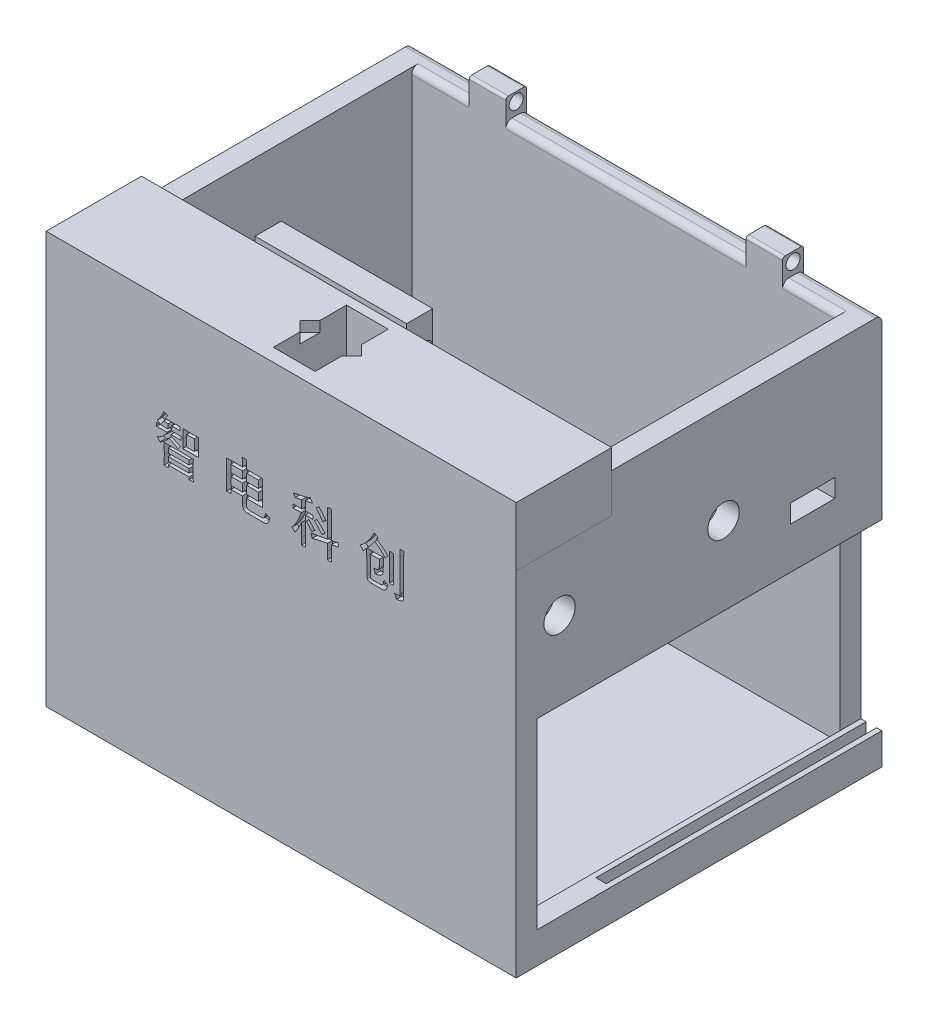
SolidWorks part; units mm, degrees
ref_plane "前视基准面" through (0, 0, 0) normal (0, 0, 1) x (1, 0, 0)
ref_plane "上视基准面" through (0, 0, 0) normal (0, 1, 0) x (1, 0, 0)
ref_plane "右视基准面" through (0, 0, 0) normal (1, 0, 0) x (0, 0, -1)
other "Configuration Table"
sketch "草图1" plane through (0, 0, 0) normal (0, 1, 0) x (1, 0, 0)
  line L1 (0, 0) -> (90, 0)
  line L2 (0, 0) -> (0, 70)
  line L3 (0, 70) -> (90, 70)
  line L4 (90, 0) -> (90, 70)
  dimension "D1" = 90
  dimension "D2" = 70
extrude "凸台-拉伸1" add sketch "草图1" along normal blind 75 contours L2 L1 L4 L3
shell "抽壳1" thickness 4
ref_plane "基准面2" through (0, 75, 0) normal (0, 1, 0) x (1, 0, 0)
sketch "草图2" plane through (0, 75, 0) normal (0, 1, 0) x (1, 0, 0)
  line L0 (0, 70) -> (90, 70) construction
  line L1 (0, 0) -> (0, 70) construction
  line L4 (4, 66) -> (86, 66) construction
  line L8 (15, 70) -> (22, 70)
  line L9 (15, 70) -> (15, 66)
  line L10 (15, 66) -> (22, 66)
  line L11 (22, 70) -> (22, 66)
  dimension "D1" = 15
  dimension "D2" = 7
extrude "凸台-拉伸2" add sketch "草图2" along normal blind 4
fillet "圆角3" radius 0.5 2 edges at (18.5, 79, -70) (18.5, 79, -66)
sketch "草图4" plane through (22, 0, 0) normal (1, 0, 0) x (0, 0, -1)
  line L0 (66, 78.5) -> (70, 78.5) construction
  line L1 (70, 78.5) -> (70, 75) construction
  line L2 (38.5, 75) -> (-38.5, 75) construction
  arc A0 (70, 78.5) -> (69.5, 79) centre (69.5, 78.5) ccw construction
  circle A1 centre (68, 77.3) radius 1.35
  dimension "D1" = 2.7
  dimension "D2" = 2.3
extrude "切除-拉伸1" cut sketch "草图4" against normal through all contours A1
ref_plane "基准面3" through (45, 0, 0) normal (-1, 0, 0) x (0, 0, 1)
mirror "镜向2" about plane through (45, 0, 0) normal (-1, 0, 0) of "切除-拉伸1", "凸台-拉伸2", "圆角3"
sketch "草图6" plane through (90, 0, 0) normal (1, 0, 0) x (0, 0, -1)
  line L1 (0, 75) -> (18.2564, 75)
  line L2 (0, 75) -> (0, 78.8304)
  line L3 (0, 78.8304) -> (18.2564, 78.8304)
  line L4 (18.2564, 75) -> (18.2564, 78.8304)
  line L5 (0, 75) -> (18.2564, 75)
  line L6 (0, 75) -> (0, 67.5141)
  line L7 (0, 67.5141) -> (18.2564, 67.5141)
  line L8 (18.2564, 75) -> (18.2564, 67.5141)
  line M3 (70, 75) -> (0, 75)
  line M4 (0, 75) -> (0, 0)
extrude "凸台-拉伸3" add sketch "草图6" along normal through all and the other way through all contours L4 L3 L2 M3 | L8 L7 M3 M4
sketch "草图7" plane through (90, 0, 0) normal (1, 0, 0) x (0, 0, -1)
  line L0 (0, 67.5141) -> (0, 0) construction
  line L5 (4, 6) -> (70, 6)
  line L6 (4, 6) -> (4, 41)
  line L7 (4, 41) -> (70, 41)
  line L8 (70, 6) -> (70, 41)
  line L9 (0, 0) -> (70, 0) construction
  dimension "D1" = 66
  dimension "D2" = 4
  dimension "D3" = 6
  dimension "D4" = 35
extrude "切除-拉伸2" cut sketch "草图7" against normal blind 4
sketch "草图8" plane through (0, 78.8304, 0) normal (0, 1, 0) x (1, 0, 0)
  line L0 (45, 38.5) -> (45, -38.5) construction
  line L1 (41, 16.5) -> (49, 16.5)
  line L2 (45, 16.5) -> (45, 2.5)
  line L3 (41, 2.5) -> (49, 2.5)
  line L4 (49, 16.5) -> (49, 2.5)
  line L5 (90, 0) -> (0, 0) construction
  line L6 (41, 16.5) -> (41, 2.5)
  dimension "D1" = 14
  dimension "D2" = 4
  dimension "D3" = 2.5
extrude "切除-拉伸3" cut sketch "草图8" against normal blind 17 contours L4 L3 L6 L1
ref_plane "基准面4" through (4, 75, -66) normal (0, 0, -1) x (-1, 0, 0)
sketch "草图10" plane through (4, 0, 0) normal (1, 0, 0) x (0, 0, -1)
  line L0 (0, 67.5141) -> (0, 0) construction
  line L1 (12, 62) -> (36, 62) construction
  line L2 (12, 62) -> (12, 50) construction
  line L3 (12, 50) -> (36, 50) construction
  line L4 (36, 62) -> (36, 50) construction
  line L5 (0, 0) -> (70, 0) construction
  line L7 (36, 62) -> (41, 62)
  line L8 (36, 62) -> (36, 50)
  line L9 (36, 50) -> (41, 50)
  line L10 (41, 62) -> (41, 50)
  line L11 (12, 62) -> (7, 62)
  line L12 (12, 62) -> (12, 50)
  line L13 (12, 50) -> (7, 50)
  line L14 (7, 62) -> (7, 50)
  dimension "D1" = 24
  dimension "D2" = 12
  dimension "D3" = 12
  dimension "D4" = 50
  dimension "D5" = 5
  dimension "D6" = 5
extrude "凸台-拉伸4" add sketch "草图10" along normal blind 29 contours L12 L11 L14 L13 | L8 L7 L10 L9
sketch "草图13" plane through (33, 0, 0) normal (1, 0, 0) x (0, 0, -1)
  line L0 (12, 56) -> (36, 56) construction
  line L1 (24, 56) -> (24, 61.1681) construction
  line L2 (39.7, 56) -> (41, 56) construction
  line L4 (36, 50) -> (41, 50)
  line L5 (41, 50) -> (41, 62)
  line L6 (41, 62) -> (36, 62)
  line L7 (36, 62) -> (36, 50)
  line L8 (36, 50) -> (41, 50)
  line L9 (41, 50) -> (41, 62)
  line L10 (41, 62) -> (36, 62)
  line L11 (36, 62) -> (36, 50)
  line L12 (7, 50) -> (12, 50)
  line L13 (12, 50) -> (12, 62)
  line L14 (12, 62) -> (7, 62)
  line L15 (7, 62) -> (7, 50)
  line L16 (7, 50) -> (12, 50)
  line L17 (12, 50) -> (12, 62)
  line L18 (12, 62) -> (7, 62)
  line L19 (7, 62) -> (7, 50)
  circle A0 centre (39.7, 56) radius 1.25
  circle A1 centre (8.3, 56) radius 1.25
  point P14 (41, 56)
  dimension "D3" = 2.5
  dimension "D4" = 1.3
  dimension "D1" = 0
  dimension "D2" = 0
extrude "切除-拉伸5" cut sketch "草图13" against normal blind 10 contours L9 A0 | A1
sketch "草图14" plane through (0, 0, -4) normal (0, 0, -1) x (-1, 0, 0)
  line L0 (-45, -38.5) -> (-45, 38.5) construction
  line L1 (-87, 46) -> (-57, 46)
  line L2 (-87, 46) -> (-87, 42)
  line L3 (-87, 42) -> (-57, 42)
  line L4 (-57, 46) -> (-57, 42)
  line L5 (0, 0) -> (-90, 0) construction
  dimension "D1" = 4
  dimension "D2" = 30
  dimension "D3" = 42
  dimension "D4" = 42
extrude "凸台-拉伸5" add sketch "草图14" along normal blind 25
sketch "草图15" plane through (0, 78.8304, 0) normal (0, 1, 0) x (1, 0, 0)
  line L0 (41, 9.5) -> (49, 9.5) construction
  line L1 (41, 16.5) -> (41, 2.5) construction
  line L2 (49, 16.5) -> (49, 2.5) construction
  line L3 (41, 2.5) -> (49, 2.5) construction
  line L4 (45, 2.5) -> (45, 16.5) construction
  line L5 (41, 16.5) -> (49, 16.5) construction
  line L7 (49, 11.413) -> (50.913, 9.5)
  line L8 (50.913, 9.5) -> (49, 7.587)
  line L9 (49, 7.587) -> (49, 11.413)
  line L10 (41, 7.587) -> (41, 11.413)
  line L11 (39.087, 9.5) -> (41, 7.587)
  line L12 (41, 11.413) -> (39.087, 9.5)
extrude "切除-拉伸6" cut sketch "草图15" against normal blind 2
fillet "圆角4" radius 1.2 6 edges at (82.5, 75, -70) (80.5, 75, -66) (7.5, 75, -70) (9.5, 75, -66) (45, 75, -70) (45, 75, -66)
sketch "草图16" plane through (90, 0, 0) normal (1, 0, 0) x (0, 0, -1)
  circle A0 centre (8.3, 56) radius 1.25 construction
  circle A1 centre (8.3, 56) radius 1.25
  circle A2 centre (39.7, 56) radius 1.25 construction
  circle A3 centre (39.7, 56) radius 1.25
  circle A4 centre (8.3, 56) radius 3
  circle A5 centre (39.7, 56) radius 3
  dimension "D1" = 6
  dimension "D2" = 6
extrude "切除-拉伸8" cut sketch "草图16" against normal blind 10 contours A4 | A5
sketch "草图17" plane through (0, 6, 0) normal (0, 1, 0) x (1, 0, 0)
  line L0 (75, 70) -> (90, 70) construction
  line L1 (87, 70) -> (89, 70)
  line L2 (87, 70) -> (87, 18.2564)
  line L3 (87, 18.2564) -> (89, 18.2564)
  line L4 (89, 70) -> (89, 18.2564)
  line L5 (90, 18.2564) -> (0, 18.2564) construction
  line L6 (90, 18.2564) -> (90, 68.8) construction
  line L7 (86, 4) -> (86, 66) construction
  dimension "D1" = 1
  dimension "D2" = 1
extrude "切除-拉伸9" cut sketch "草图17" against normal blind 2
ref_plane "基准面5" through (0, 23.5, 0) normal (0, 1, 0) x (1, 0, 0)
mirror "镜向3" about plane through (0, 23.5, 0) normal (0, 1, 0) of "切除-拉伸9"
sketch "草图18" plane through (90, 0, 0) normal (1, 0, 0) x (0, 0, -1)
  line L0 (70, 41) -> (4, 41) construction
  line L1 (52.5, 52.5) -> (61, 52.5)
  line L2 (52.5, 52.5) -> (52.5, 49)
  line L3 (52.5, 49) -> (61, 49)
  line L4 (61, 52.5) -> (61, 49)
  line L5 (70, 73.8) -> (70, 41) construction
  dimension "D1" = 8.5
  dimension "D2" = 3.5
  dimension "D3" = 8
  dimension "D4" = 9
extrude "切除-拉伸10" cut sketch "草图18" against normal up to next
sketch "草图22" plane through (0, 0, 0) normal (0, 0, 1) x (1, 0, 0)
  text T0 "智电科创" font "黑体" height 6.5
extrude "切除-拉伸13" cut sketch "草图22" against normal blind 1
